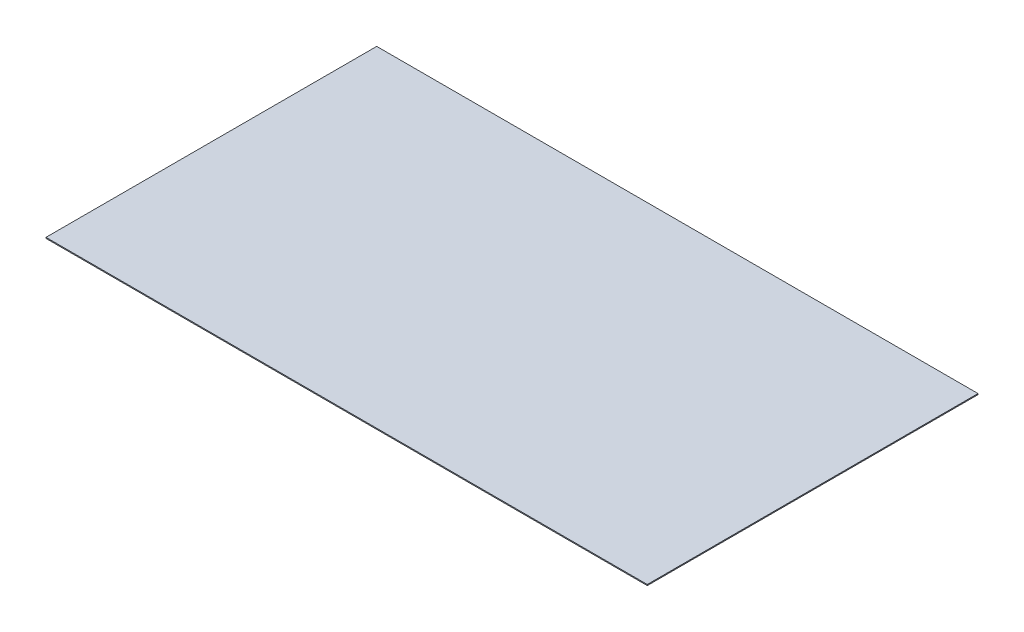
SolidWorks part; units mm, degrees
material "1100-H16 Rod (SS)"
ref_plane "Front Plane" through (0, 0, 0) normal (0, 0, 1) x (1, 0, 0)
ref_plane "Top Plane" through (0, 0, 0) normal (0, 1, 0) x (1, 0, 0)
ref_plane "Right Plane" through (0, 0, 0) normal (1, 0, 0) x (0, 0, -1)
sketch "Sketch1" plane through (0, 0, 0) normal (0, 1, 0) x (1, 0, 0)
  line L1 (-38.1, -20.955) -> (38.1, -20.955)
  line L2 (-38.1, -20.955) -> (-38.1, 20.955)
  line L3 (-38.1, 20.955) -> (38.1, 20.955)
  line L4 (38.1, -20.955) -> (38.1, 20.955)
  line L5 (-38.1, -20.955) -> (38.1, 20.955) construction
  line L6 (-38.1, 20.955) -> (38.1, -20.955) construction
  point P0 (0, 0)
  dimension "D1" = 41.91
  dimension "D2" = 76.2
extrude "Boss-Extrude1" add sketch "Sketch1" along normal blind 0.127
